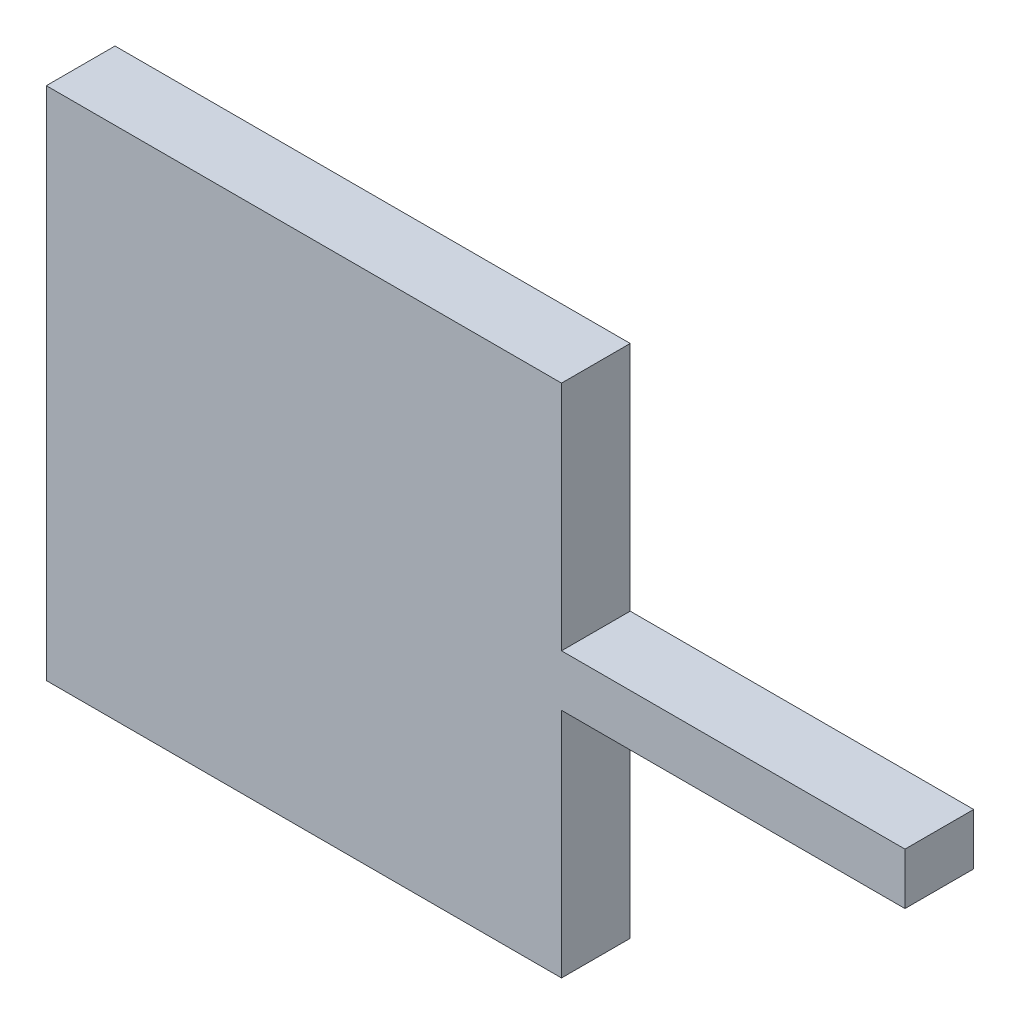
SolidWorks part; units mm, degrees
ref_plane "Front Plane" through (0, 0, 0) normal (0, 0, 1) x (1, 0, 0)
ref_plane "Top Plane" through (0, 0, 0) normal (0, 1, 0) x (1, 0, 0)
ref_plane "Right Plane" through (0, 0, 0) normal (1, 0, 0) x (0, 0, -1)
sketch "Sketch1" plane through (0, 0, 0) normal (0, 1, 0) x (1, 0, 0)
  line L1 (0, 0) -> (2, 0)
  line L2 (0, 0) -> (0, -0.4)
  line L3 (0, -0.4) -> (2, -0.4)
  line L4 (2, 0) -> (2, -0.4)
  dimension "D1" = 2
  dimension "D2" = 0.4
extrude "Boss-Extrude1" add sketch "Sketch1" along normal blind 0.3
sketch "Sketch3" plane through (0, 0, 0) normal (-1, 0, 0) x (0, 0, 1)
  line L0 (0, 0.3) -> (0, 0) construction
  line L1 (0, 1.65) -> (0.4, 1.65)
  line L2 (0, 1.65) -> (0, -1.35)
  line L3 (0, -1.35) -> (0.4, -1.35)
  line L4 (0.4, 1.65) -> (0.4, -1.35)
  line L5 (0.4, 0.3) -> (0.4, 0) construction
  line L6 (0.2, 1.65) -> (0.2, 0.3)
  line L7 (0, 0.3) -> (0.4, 0.3) construction
  line L8 (0.2, 0) -> (0.2, -1.35)
  line L9 (0, 0) -> (0.4, 0) construction
  line M7 (0, 0) -> (0.4, 0)
  line M8 (0.4, 0) -> (0.4, 0.3)
  line M9 (0.4, 0.3) -> (0, 0.3)
  line M10 (0, 0.3) -> (0, 0)
  dimension "D1" = 3
extrude "Boss-Extrude4" add sketch "Sketch3" along normal blind 3 contours L8 L3 L4 M7 | L8 L2 L3 M7 | M10 M7 M8 M9 | L6 L1 L2 M9 | L1 L6 L4 M9
